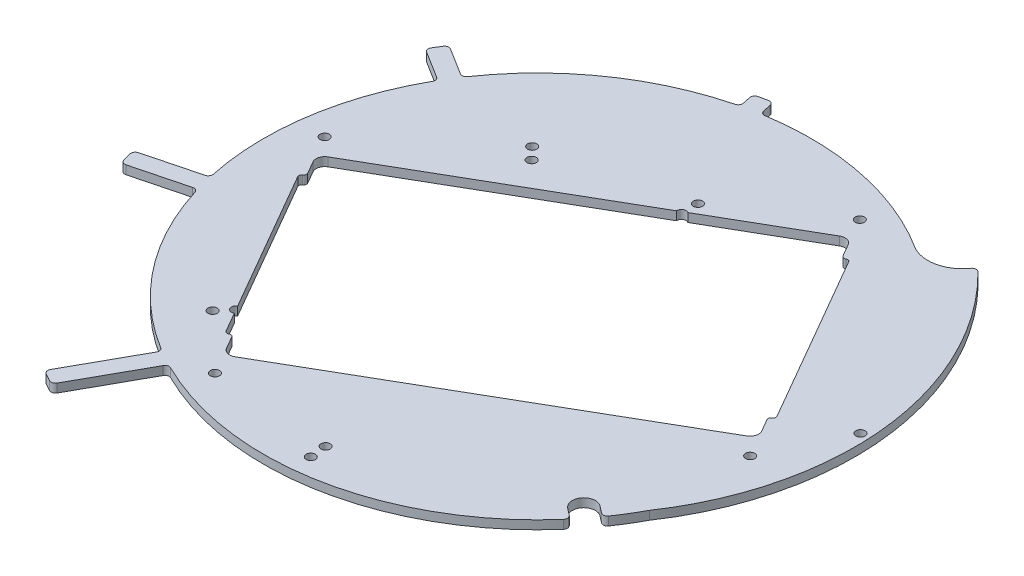
SolidWorks part; units mm, degrees
ref_plane "Ebene vorne" through (0, 0, 0) normal (0, 0, 1) x (1, 0, 0)
ref_plane "Ebene oben" through (0, 0, 0) normal (0, 1, 0) x (1, 0, 0)
ref_plane "Ebene rechts" through (0, 0, 0) normal (1, 0, 0) x (0, 0, -1)
sketch "Skizze1" plane through (0, 0, 0) normal (0, 1, 0) x (1, 0, 0)
  spline S0 degree 4 poles (14.6946, -20.2254) (15.1972, -20.0972) (16.1945, -19.8118) (18.155, -19.1263) (21.9045, -17.3262) (26.5458, -13.9147) (31.2339, -8.2405) (34.3034, -1.3721) (35.6462, 5.1086) (35.8337, 10.8368) (35.3425, 15.6755) (34.2212, 20.452) (32.4895, 25.089) (30.1753, 29.5135) (27.3142, 33.6581) (24.2984, 37.075) (21.3064, 39.8427) (18.4695, 42.0524) (15.8825, 43.7935) (13.1828, 45.3539) (10.3841, 46.7291) (8.0412, 47.6929) (6.2056, 48.3447) (4.9057, 48.759) (4.1664, 48.9823) (3.5009, 49.1701) (2.9324, 49.3228) (2.3788, 49.4662) (1.9696, 49.5678) (1.585, 49.6585) (1.1824, 49.7497) (0.7731, 49.84) (0.2506, 49.9509) (-0.176, 50.0361) (-0.7126, 50.1366) (-1.2516, 50.2331) (-1.7764, 50.322) (-2.3404, 50.4092) (-3.0019, 50.5028) (-3.858, 50.6138) (-4.8637, 50.7239) (-6.0487, 50.8274) (-7.4035, 50.9087) (-8.7603, 50.9537) (-10.1178, 50.9625) (-11.475, 50.9352) (-12.8311, 50.872) (-14.185, 50.7732) (-15.5359, 50.639) (-16.8828, 50.4696) (-18.5604, 50.2144) (-21.309, 49.6989) (-24.3915, 48.921) (-27.7729, 47.8097) (-31.7695, 46.1769) (-34.9991, 44.5869) (-38.1118, 42.7788) (-41.9978, 40.1541) (-45.9692, 37.0083) (-50.3969, 32.7165) (-54.9533, 27.0648) (-58.7999, 20.9088) (-61.8962, 14.3441) (-64.2145, 7.4667) (-65.7383, 0.3714) (-66.4622, -6.8491) (-66.3905, -14.105) (-65.5369, -21.3106) (-63.923, -28.3846) (-61.5784, -35.2506) (-58.5386, -41.8382) (-53.9221, -49.6436) (-47.168, -58.2065) (-37.7396, -66.7961) (-25.2947, -74.3771) (-11.6604, -79.5091) (3.2843, -82.1851) (19.0946, -82.0003) (36.3648, -78.3877) (54.135, -70.3578) (70.574, -57.7146) (84.2397, -40.5569) (93.5043, -20.6856) (97.9802, 0.7684) (97.5541, 22.6716) (92.3547, 43.9462) (80.3282, 68.5258) (58.085, 93.109) (23.6719, 111.5895) (-20.6724, 115.9503) (-63.3844, 103.5087) (-98.6718, 76.5218) (-122.2192, 38.9179) (-131.5042, -4.417) (-125.85, -48.3283) (-106.2669, -87.9909) (-75.1445, -119.3721) (-35.8562, -139.5431) (7.6702, -146.8361) (51.3698, -140.8641) (91.4081, -122.4257) (124.4839, -93.3238) (148.0467, -56.1245) (160.4282, -13.8885) (160.892, 30.1038) (149.6093, 72.6084) (128.6442, 108.7973) (101.0923, 137.2266) (67.9766, 158.7743) (30.8728, 172.5378) (-10.5987, 177.5413) (-54.1378, 171.942) (-105.2309, 151.9976) (-147.9956, 116.5416) (-177.4727, 69.5356) (-193.8883, 5.8675) (-190.4304, -60.5646) (-157.7421, -132.0491) (-89.225, -189.9457) (-2.9015, -213.9008) (85.5525, -200.4114) (161.0378, -152.5558) (211.447, -78.8635) (229.3029, 8.5291) (212.488, 96.0469) (164.0999, 170.796) (91.5801, 222.345) (5.3403, 243.9674) (-82.859, 233.2545) (-161.5374, 192.1036) (-220.9195, 126.1657) (-254.0125, 43.8869) (-257.2482, -44.6901) (-233.9893, -118.6349) (-197.5487, -173.5363) (-158.1112, -211.2478) (-122.0151, -235.7981) (-72.4806, -258.6706) (-18.8569, -270.3704) (36.0125, -270.2335) (89.2898, -258.5247) (129.878, -242.4941) (167.415, -220.2445) (200.9833, -192.3672) (226.1758, -163.6811) (244.3621, -136.5439) (257.0787, -112.5154) (265.7319, -92.562) (274.5884, -66.8593) (282.0045, -35.0464) (285.3007, -2.4946) (284.4351, 30.1581) (280.9666, 57.1207) (276.5638, 78.4183) (270.5627, 99.3216) (263.0017, 119.7125) (253.9277, 139.4764) (243.3959, 158.5035) (231.4693, 176.6887) (218.2181, 193.9324) (203.7194, 210.1412) (188.0566, 225.2279) (171.3189, 239.1124) (153.6007, 251.7215) (137.3261, 261.5812) (122.8899, 269.1582) (110.5687, 274.874) (100.5506, 279.0819) (90.3851, 282.9199) (80.0858, 286.3833) (69.667, 289.4679) (59.1422, 292.1701) (49.8533, 294.1971) (41.8425, 295.6919) (35.1401, 296.7751) (29.7611, 297.5441) (25.0482, 298.1312) (20.9908, 298.5735) (17.6219, 298.9007) (14.927, 299.1378) (12.1541, 299.3528) (9.4847, 299.5398) (6.9207, 299.6987) (4.0187, 299.8442) (1.0689, 299.9667) (-1.1013, 300.0385) (-4.0869, 300.1123) (-7.0224, 300.159) (-9.6213, 300.1693) (-12.3458, 300.1584) (-15.1662, 300.1255) (-17.9045, 300.0646) (-21.3378, 299.9573) (-25.4729, 299.7787) (-30.2807, 299.4963) (-35.7759, 299.0732) (-41.2587, 298.5495) (-46.7331, 297.9257) (-52.1939, 297.2019) (-57.6414, 296.3785) (-63.0725, 295.4558) (-68.4861, 294.4342) (-73.88, 293.314) (-79.2527, 292.0957) (-84.6023, 290.7798) (-89.9271, 289.3667) (-101.848, 285.9698) (-117.516, 280.6722) (-136.6285, 272.7576) (-158.6701, 261.3664) (-177.4812, 249.8542) (-195.4151, 237.0185) (-212.3814, 222.9286) (-228.2949, 207.6598) (-243.0767, 191.293) (-256.654, 173.9142) (-268.9609, 155.6137) (-279.938, 136.4861) (-289.5332, 116.6294) (-297.7017, 96.1445) (-304.4059, 75.1348) (-308.3134, 59.0631) (-310.4129, 48.2443) (-311.3357, 42.8134) knots 0 0 0 0 0 0.000419 0.000839 0.001678 0.003355 0.005034 0.006714 0.007694 0.008675 0.009656 0.010636 0.011652 0.012668 0.013684 0.0147 0.01533 0.01596 0.01659 0.01722 0.01785 0.01848 0.018637 0.018795 0.018952 0.01911 0.019189 0.019268 0.019425 0.019464 0.019504 0.019583 0.01974 0.019877 0.019946 0.020015 0.020152 0.020289 0.020426 0.020563 0.020838 0.021112 0.021387 0.021661 0.021936 0.02221 0.022485 0.022759 0.023034 0.023308 0.023583 0.024131 0.025295 0.025877 0.026458 0.027622 0.028203 0.028785 0.03025 0.031714 0.033178 0.034643 0.036107 0.037571 0.039035 0.0405 0.041964 0.043429 0.044893 0.046357 0.047822 0.049286 0.052215 0.055144 0.058073 0.061002 0.063932 0.067358 0.070784 0.075177 0.07957 0.083963 0.088356 0.09275 0.097143 0.101536 0.10593 0.114717 0.123503 0.13229 0.141076 0.149863 0.15865 0.167436 0.176223 0.18501 0.193797 0.202583 0.21137 0.220157 0.228944 0.23773 0.246517 0.255304 0.264091 0.272877 0.281664 0.288742 0.29582 0.304606 0.313393 0.32218 0.330966 0.348539 0.357326 0.366112 0.383686 0.401259 0.418832 0.436405 0.453979 0.471552 0.489125 0.506698 0.524272 0.541845 0.559418 0.576992 0.594565 0.612138 0.629712 0.647285 0.664859 0.682432 0.691219 0.700005 0.708792 0.717579 0.735152 0.743939 0.752725 0.761512 0.770299 0.779086 0.787872 0.792266 0.796659 0.801052 0.805446 0.814233 0.823019 0.827413 0.831806 0.836199 0.840593 0.844986 0.849379 0.853773 0.858166 0.862559 0.866953 0.871346 0.87574 0.880133 0.884526 0.886723 0.88892 0.891116 0.893313 0.89551 0.897706 0.899903 0.9021 0.903198 0.904297 0.905395 0.906493 0.907042 0.907592 0.908141 0.90869 0.909239 0.909788 0.910337 0.910887 0.911444 0.912001 0.912557 0.913114 0.913671 0.914228 0.914785 0.915342 0.916456 0.91757 0.918684 0.919798 0.920912 0.922026 0.92314 0.924254 0.925368 0.926481 0.927595 0.928709 0.929823 0.930937 0.937621 0.942076 0.946532 0.950988 0.955443 0.959899 0.964355 0.96881 0.973266 0.977722 0.982177 0.986633 0.991089 0.995544 1 1 1 1 1 construction
  spline S1 degree 4 poles (0, 50) (-0.1483, 50.0295) (-0.3717, 50.0727) (-0.7126, 50.1366) (-1.2516, 50.2331) (-1.7764, 50.322) (-2.3404, 50.4092) (-3.0019, 50.5028) (-3.858, 50.6138) (-4.8637, 50.7239) (-6.0487, 50.8274) (-7.4035, 50.9087) (-8.7603, 50.9537) (-10.1178, 50.9625) (-11.475, 50.9352) (-12.8311, 50.872) (-14.185, 50.7732) (-15.5359, 50.639) (-16.8828, 50.4696) (-18.5604, 50.2144) (-21.309, 49.6989) (-24.3915, 48.921) (-27.7729, 47.8097) (-31.7695, 46.1769) (-34.9991, 44.5869) (-38.1118, 42.7788) (-41.9978, 40.1541) (-45.9692, 37.0083) (-50.3969, 32.7165) (-54.9533, 27.0648) (-58.7999, 20.9088) (-61.8962, 14.3441) (-64.2145, 7.4667) (-65.7383, 0.3714) (-66.4622, -6.8491) (-66.3905, -14.105) (-65.5369, -21.3106) (-63.923, -28.3846) (-61.5784, -35.2506) (-58.5386, -41.8382) (-53.9221, -49.6436) (-47.168, -58.2065) (-37.7396, -66.7961) (-25.2947, -74.3771) (-11.6604, -79.5091) (3.2843, -82.1851) (19.0946, -82.0003) (36.3648, -78.3877) (54.135, -70.3578) (70.574, -57.7146) (84.2397, -40.5569) (93.5043, -20.6856) (97.9802, 0.7684) (97.5541, 22.6716) (92.3547, 43.9462) (80.3282, 68.5258) (58.085, 93.109) (23.6719, 111.5895) (-20.6724, 115.9503) (-63.3844, 103.5087) (-98.6718, 76.5218) (-122.2192, 38.9179) (-131.5042, -4.417) (-125.85, -48.3283) (-106.2669, -87.9909) (-75.1445, -119.3721) (-35.8562, -139.5431) (7.6702, -146.8361) (51.3698, -140.8641) (91.4081, -122.4257) (124.4839, -93.3238) (148.0467, -56.1245) (160.4282, -13.8885) (160.892, 30.1038) (149.6093, 72.6084) (128.6442, 108.7973) (101.0923, 137.2266) (67.9766, 158.7743) (30.8728, 172.5378) (-10.5987, 177.5413) (-54.1378, 171.942) (-105.2309, 151.9976) (-147.9956, 116.5416) (-177.4727, 69.5356) (-193.8883, 5.8675) (-190.4304, -60.5646) (-157.7421, -132.0491) (-89.225, -189.9457) (-2.9015, -213.9008) (85.5525, -200.4114) (161.0378, -152.5558) (211.447, -78.8635) (229.3029, 8.5291) (212.488, 96.0469) (164.0999, 170.796) (91.5801, 222.345) (5.3403, 243.9674) (-82.859, 233.2545) (-161.5374, 192.1036) (-220.9195, 126.1657) (-254.0125, 43.8869) (-257.2482, -44.6901) (-233.9893, -118.6349) (-197.5487, -173.5363) (-158.1112, -211.2478) (-122.0151, -235.7981) (-72.4806, -258.6706) (-18.8569, -270.3704) (36.0125, -270.2335) (89.2898, -258.5247) (129.878, -242.4941) (167.415, -220.2445) (200.9833, -192.3672) (226.1758, -163.6811) (244.3621, -136.5439) (257.0787, -112.5154) (265.7319, -92.562) (274.5884, -66.8593) (282.0045, -35.0464) (285.3007, -2.4946) (284.4351, 30.1581) (280.9666, 57.1207) (276.5638, 78.4183) (270.5627, 99.3216) (263.0017, 119.7125) (253.9277, 139.4764) (243.3959, 158.5035) (231.4693, 176.6887) (218.2181, 193.9324) (203.7194, 210.1412) (188.0566, 225.2279) (171.3189, 239.1124) (153.6007, 251.7215) (137.3261, 261.5812) (122.8899, 269.1582) (110.5687, 274.874) (100.5506, 279.0819) (90.3851, 282.9199) (80.0858, 286.3833) (69.667, 289.4679) (59.1422, 292.1701) (49.8533, 294.1971) (41.8425, 295.6919) (35.1401, 296.7751) (29.7611, 297.5441) (25.0482, 298.1312) (20.9908, 298.5735) (17.6219, 298.9007) (14.927, 299.1378) (12.1541, 299.3528) (9.4847, 299.5398) (6.9207, 299.6987) (4.0187, 299.8442) (1.8142, 299.9357) (0.6047, 299.9799) (0, 300) knots 0.01974 0.01974 0.01974 0.01974 0.01974 0.019877 0.019946 0.020015 0.020152 0.020289 0.020426 0.020563 0.020838 0.021112 0.021387 0.021661 0.021936 0.02221 0.022485 0.022759 0.023034 0.023308 0.023583 0.024131 0.025295 0.025877 0.026458 0.027622 0.028203 0.028785 0.03025 0.031714 0.033178 0.034643 0.036107 0.037571 0.039035 0.0405 0.041964 0.043429 0.044893 0.046357 0.047822 0.049286 0.052215 0.055144 0.058073 0.061002 0.063932 0.067358 0.070784 0.075177 0.07957 0.083963 0.088356 0.09275 0.097143 0.101536 0.10593 0.114717 0.123503 0.13229 0.141076 0.149863 0.15865 0.167436 0.176223 0.18501 0.193797 0.202583 0.21137 0.220157 0.228944 0.23773 0.246517 0.255304 0.264091 0.272877 0.281664 0.288742 0.29582 0.304606 0.313393 0.32218 0.330966 0.348539 0.357326 0.366112 0.383686 0.401259 0.418832 0.436405 0.453979 0.471552 0.489125 0.506698 0.524272 0.541845 0.559418 0.576992 0.594565 0.612138 0.629712 0.647285 0.664859 0.682432 0.691219 0.700005 0.708792 0.717579 0.735152 0.743939 0.752725 0.761512 0.770299 0.779086 0.787872 0.792266 0.796659 0.801052 0.805446 0.814233 0.823019 0.827413 0.831806 0.836199 0.840593 0.844986 0.849379 0.853773 0.858166 0.862559 0.866953 0.871346 0.87574 0.880133 0.884526 0.886723 0.88892 0.891116 0.893313 0.89551 0.897706 0.899903 0.9021 0.903198 0.904297 0.905395 0.906493 0.907042 0.907592 0.908141 0.90869 0.909239 0.909788 0.910337 0.910887 0.910887 0.910887 0.910887 0.910887
  point P0 (0, 0)
sketch "Skizze3" plane through (0, 0, 0) normal (0, 1, 0) x (1, 0, 0)
  line L0 (-1.5959, 49.8854) -> (-78.2917, 5.6051)
  line L1 (-22.9202, 96.6291) -> (-22.3443, 93.8164)
  line L2 (-21.7526, 98.3993) -> (-18.813, 99.0034)
  line L3 (-91.5676, 58.8399) -> (-93.1544, 56.294)
  line L4 (-113.5351, -27.851) -> (-112.783, -30.7552)
  line L5 (-61.9583, -108.5299) -> (-59.3353, -109.9859)
  line L6 (-57.2958, -109.4024) -> (-44.1599, -85.7374)
  line L7 (-62.5418, -106.4904) -> (-49.4059, -82.8255)
  line L8 (-110.9549, -31.8312) -> (-92.5649, -27.0691)
  line L9 (-112.459, -26.0228) -> (-94.069, -21.2607)
  line L10 (-92.6749, 54.2276) -> (-83.3928, 48.4422)
  line L11 (-89.5012, 59.3195) -> (-80.2191, 53.5341)
  line L12 (-17.0418, 97.836) -> (-16.4643, 95.0259)
  line L14 (-47.53, -57.6756) -> (-43.6218, -64.4449)
  line L16 (73.8686, -52.127) -> (76.2547, -53.9742)
  line L17 (68.9714, -58.453) -> (71.3575, -60.3002)
  line L27 (-40.8897, -65.1769) -> (-38.3897, -69.507)
  line L41 (-77.6218, -5.5551) -> (-49.13, -54.9044)
  line L42 (-79.3897, 1.507) -> (-76.8897, -2.8231)
  line L43 (79.3897, -1.507) -> (76.8897, 2.8231)
  line L44 (-34.2917, -70.6051) -> (78.2917, -5.6051)
  line L45 (77.6218, 5.5551) -> (43.6218, 64.4449)
  line L46 (40.8897, 65.1769) -> (38.3897, 69.507)
  line L47 (34.2917, 70.6051) -> (0.8972, 51.3248)
  circle A0 centre (-84.8897, 11.0333) radius 1.6
  circle A1 centre (32.8897, 79.0333) radius 1.6
  circle A2 centre (84.8897, -11.0333) radius 1.6
  circle A3 centre (-32.8897, -79.0333) radius 1.6
  arc A4 (-90.7559, -28.0778) -> (-49.929, -80.8214) centre (0, 0) ccw
  arc A5 (-82.8776, 46.436) -> (-92.977, -19.5007) centre (0, 0) ccw
  arc A6 (-42.1823, -85.1214) -> (71.5693, -62.4727) centre (0, 0) ccw
  arc A7 (-44.1599, -85.7374) -> (-42.1823, -85.1214) centre (-42.8484, -86.4654) cw
  arc A8 (-59.3353, -109.9859) -> (-57.2958, -109.4024) centre (-58.6073, -108.6744) ccw
  arc A9 (-61.9583, -108.5299) -> (-62.5418, -106.4904) centre (-61.2303, -107.2184) cw
  arc A10 (-49.4059, -82.8255) -> (-49.929, -80.8214) centre (-50.7174, -82.0975) ccw
  arc A11 (-92.5649, -27.0691) -> (-90.7559, -28.0778) centre (-92.1889, -28.5212) cw
  arc A12 (-112.783, -30.7552) -> (-110.9549, -31.8312) centre (-111.3309, -30.3791) ccw
  arc A13 (-94.069, -21.2607) -> (-92.977, -19.5007) centre (-94.4451, -19.8086) ccw
  arc A14 (-113.5351, -27.851) -> (-112.459, -26.0228) centre (-112.083, -27.4749) cw
  arc A15 (-83.3928, 48.4422) -> (-82.8776, 46.436) centre (-84.1862, 47.1692) cw
  arc A16 (-93.1544, 56.294) -> (-92.6749, 54.2276) centre (-91.8815, 55.5005) ccw
  arc A17 (-91.5676, 58.8399) -> (-89.5012, 59.3195) centre (-90.2946, 58.0465) cw
  arc A18 (-80.2191, 53.5341) -> (-78.1911, 53.9552) centre (-79.4257, 54.8071) ccw
  arc A19 (-18.813, 99.0034) -> (-17.0418, 97.836) centre (-18.5111, 97.5341) cw
  arc A20 (-21.7526, 98.3993) -> (-22.9202, 96.6291) centre (-21.4507, 96.93) ccw
  arc A21 (-22.3443, 93.8164) -> (-23.4436, 92.0619) centre (-23.8138, 93.5155) cw
  arc A22 (-16.4643, 95.0259) -> (-14.762, 93.8461) centre (-14.9951, 95.3278) ccw
  arc A23 (51.1398, 80.0607) -> (-14.762, 93.8461) centre (0, 0) ccw
  arc A24 (-43.6218, -64.4449) -> (-42.2558, -64.8109) centre (-42.7558, -63.9449) ccw
  arc A25 (-42.2558, -64.8109) -> (-40.8897, -65.1769) centre (-41.7558, -65.6769) cw
  arc A26 (-38.3897, -69.507) -> (-34.2917, -70.6051) centre (-35.7917, -68.007) ccw
  arc A27 (-23.4436, 92.0619) -> (-78.1911, 53.9552) centre (0, 0) ccw
  arc A28 (69.0595, 83.8939) -> (66.7734, 83.6844) centre (68.0045, 82.8275) ccw
  arc A29 (66.7734, 83.6844) -> (51.1398, 80.0607) centre (56.9522, 90.52) cw
  circle A30 centre (97.25, 14.9) radius 1.6
  circle A32 centre (8.32, -81.84) radius 1.6
  arc A42 (-77.2558, -4.1891) -> (-77.6218, -5.5551) centre (-76.7558, -5.0551) ccw
  arc A43 (-77.2558, -4.1891) -> (-76.8897, -2.8231) centre (-77.7558, -3.3231) ccw
  arc A44 (-78.2917, 5.6051) -> (-79.3897, 1.507) centre (-76.7917, 3.007) ccw
  arc A45 (77.2558, 4.1891) -> (77.6218, 5.5551) centre (76.7558, 5.0551) ccw
  arc A46 (77.2558, 4.1891) -> (76.8897, 2.8231) centre (77.7558, 3.3231) ccw
  arc A47 (78.2917, -5.6051) -> (79.3897, -1.507) centre (76.7917, -3.007) ccw
  arc A48 (43.6218, 64.4449) -> (42.2558, 64.8109) centre (42.7558, 63.9449) ccw
  arc A49 (40.8897, 65.1769) -> (42.2558, 64.8109) centre (41.7558, 65.6769) ccw
  arc A50 (38.3897, 69.507) -> (34.2917, 70.6051) centre (35.7917, 68.007) ccw
  arc A51 (-49.13, -54.9044) -> (-47.53, -57.6756) centre (-48.33, -56.29) ccw
  circle A52 centre (-42, 40) radius 1.6
  arc A53 (0.8972, 51.3248) -> (-1.5959, 49.8854) centre (0, 50) ccw
  circle A54 centre (0, 55.75) radius 1.6
  circle A55 centre (-45.9655, 44.1638) radius 1.6
  circle A56 centre (-52.0757, -60.6526) radius 1.6
  circle A57 centre (8.9016, -87.5605) radius 1.6
  arc A59 (78.411, -53.635) -> (83.7428, -44.857) centre (0, 0) ccw
  arc A60 (73.8686, -52.127) -> (68.9714, -58.453) centre (71.42, -55.29) ccw
  arc A62 (76.2547, -53.9742) -> (78.411, -53.635) centre (77.1729, -52.7881) ccw
  arc A63 (71.3575, -60.3002) -> (71.5693, -62.4727) centre (70.4393, -61.4863) cw
  spline S0 degree 3 poles (83.7428, -44.857) (85.08, -42.8857) (86.3427, -40.8642) (90.4754, -33.6587) (92.9411, -28.2452) (96.8451, -17.0642) (98.2834, -11.2967) (100.1065, 0.3981) (100.4914, 6.3254) (100.2158, 18.1518) (99.5553, 24.0508) (97.2281, 35.6432) (95.5615, 41.3363) (91.2892, 52.3544) (88.6836, 57.6794) (82.6218, 67.8176) (79.1658, 72.6308) (73.3439, 79.471) (71.2477, 81.7292) (69.0595, 83.8939) knots 0.068743 0.068743 0.068743 0.068743 0.070312 0.070312 0.074219 0.074219 0.078125 0.078125 0.082031 0.082031 0.085937 0.085937 0.089844 0.089844 0.09375 0.09375 0.097656 0.097656 0.099693 0.099693 0.099693 0.099693
  spline S2 degree 3 poles (3903.7256, -759.8806) (-42.2405, 56.3514) (13.4469, 50.5335) (-0.1234, 53.078) (-0.32, 53.114) (-0.7166, 53.1845) (-0.9153, 53.2187) (-1.3018, 53.2828) (-1.49, 53.3127) (-2.0445, 53.3975) (-2.4092, 53.4491) (-3.1633, 53.5489) (-3.5476, 53.5957) (-4.3046, 53.6788) (-4.6812, 53.716) (-5.4375, 53.7827) (-5.8167, 53.8121) (-6.9547, 53.888) (-7.7138, 53.9223) (-11.511, 54.0137) (-14.552, 53.8287) (-20.5572, 52.9655) (-23.5214, 52.2872) (-29.3, 50.4707) (-32.1142, 49.3325) (-37.5292, 46.6377) (-40.13, 45.0812) (-45.0646, 41.5974) (-47.3984, 39.6702) (-51.7555, 35.4974) (-53.7787, 33.2519) (-57.4808, 28.4973) (-59.1597, 25.9883) (-62.1481, 20.7632) (-63.4578, 18.0471) (-65.6918, 12.4643) (-66.6162, 9.5975) (-68.7994, 0.8547) (-69.465, -5.1626) (-69.2373, -17.1545) (-68.3449, -23.1285) (-65.1185, -34.6611) (-62.7853, -40.2193) (-56.8668, -50.6106) (-53.2822, -55.4435) (-45.1003, -64.144) (-40.5036, -68.0116) (-30.5672, -74.6131) (-25.2281, -77.3471) (-14.0895, -81.5827) (-8.2905, -83.0844) (3.487, -84.8214) (9.4653, -85.0569) (21.3343, -84.2856) (27.225, -83.2791) (38.6755, -80.0977) (44.2352, -77.9231) (54.8103, -72.5211) (59.8256, -69.294) (69.1339, -61.9344) (73.4268, -57.8024) (81.1496, -48.8041) (84.5796, -43.9382) (90.4754, -33.6587) (92.9411, -28.2452) (96.8451, -17.0642) (98.2834, -11.2967) (100.1065, 0.3981) (100.4914, 6.3254) (100.2158, 18.1518) (99.5553, 24.0508) (97.2281, 35.6432) (95.5615, 41.3363) (91.2892, 52.3544) (88.6836, 57.6794) (82.6218, 67.8176) (79.1658, 72.6308) (71.5131, 81.622) (67.3166, 85.8) (58.3057, 93.4207) (53.4912, 96.8634) (43.3772, 102.9364) (38.078, 105.5667) (27.1354, 109.9618) (21.492, 111.7266) (10.0022, 114.3604) (4.1559, 115.2293) (-7.5984, 116.0638) (-13.5061, 116.0296) (-25.2464, 115.0712) (-31.0789, 114.1471) (-42.5397, 111.4415) (-48.1678, 109.6602) (-59.0988, 105.291) (-64.4017, 102.7033) (-74.5741, 96.7862) (-79.4435, 93.4568) (-88.6529, 86.1356) (-97.3327, 78.1521) (-104.7905, 69.0219) (-111.5707, 59.4154) (-114.622, 54.3742) (-119.9956, 43.9194) (-122.3181, 38.506) (-126.1983, 27.4132) (-127.7561, 21.734) (-130.0868, 10.2184) (-131.6327, -1.4541) (-131.5981, -13.2248) (-130.7818, -24.9398) (-129.9829, -30.7693) (-127.6259, -42.2709) (-124.5099, -53.6151) (-119.9439, -64.4543) (-114.6988, -74.9526) (-108.7748, -85.1098) (-101.6036, -94.4246) (-93.8725, -103.2472) (-89.727, -107.4124) (-80.9478, -115.1892) (-71.6802, -122.4123) (-61.5887, -128.4262) (-51.1662, -133.795) (-40.4131, -138.5187) (-29.1662, -141.8931) (-17.7572, -144.5737) (-11.9718, -145.5672) (-0.3249, -146.8523) (11.398, -147.4354) (23.1049, -146.6182) (34.7214, -145.1125) (46.2475, -142.9184) (57.4348, -139.3893) (68.3781, -135.2221) (73.7277, -132.8194) (84.1131, -127.4134) (94.1844, -121.4068) (103.5001, -114.2876) (112.3804, -106.6626) (120.8252, -98.5321) (128.2975, -89.5024) (135.2401, -80.0833) (138.4466, -75.1791) (144.2939, -65.0454) (146.9347, -59.816) (153.9663, -43.7395) (157.4625, -32.5037) (161.9389, -9.5462) (162.9194, 2.175) (162.3541, 25.5523) (160.8087, 37.2075) (155.296, 59.9268) (151.3292, 70.99) (141.1807, 92.0449) (134.9995, 102.0361) (120.7171, 120.5309) (112.6161, 129.0342) (94.858, 144.2158) (85.2014, 150.8938) (64.7464, 162.1728) (53.9485, 166.7736) (31.658, 173.7397) (20.1658, 176.1051) (-3.0569, 178.5334) (-14.7866, 178.5964) (-38.0325, 176.4435) (-49.5478, 174.2284) (-71.9354, 167.6295) (-82.8075, 163.2458) (-103.5186, 152.4915) (-113.3574, 146.1211) (-131.6584, 131.6464) (-140.1202, 123.5429) (-155.3849, 105.9036) (-162.1878, 96.368) (-173.9182, 76.2059) (-178.8455, 65.5807) (-186.676, 43.6136) (-189.5792, 32.2718) (-193.2853, 9.2511) (-194.0884, -2.4278) (-193.5897, -25.7377) (-192.2882, -37.368) (-187.6411, -60.2099) (-184.2956, -71.4216) (-175.6836, -93.0808) (-170.4178, -103.5277) (-158.1475, -123.3402) (-151.143, -132.7056) (-135.6204, -150.0833) (-127.1024, -158.0955) (-108.8209, -172.5402) (-99.0582, -178.9724) (-78.5836, -190.0823) (-67.8717, -194.76) (-45.8128, -202.2421) (-34.4665, -205.0465) (-11.4679, -208.7186) (0.1842, -209.5862) (23.4699, -209.3759) (35.1035, -208.2981) (58.033, -204.2429) (69.3283, -201.2659) (91.2789, -193.5079) (101.9342, -188.7269) (122.3286, -177.501) (132.0674, -171.0565) (150.3795, -156.687) (158.9528, -148.7621) (174.7231, -131.6454) (181.92, -122.4537) (194.7655, -103.0469) (200.4137, -92.8324) (210.0315, -71.6438) (214.0011, -60.6697) (220.1762, -38.2362) (222.3818, -26.7772) (224.9884, -3.6581) (225.3894, 8.0017) (224.3894, 31.2429) (222.9885, 42.8243) (218.4309, 65.6353) (215.2745, 76.8643) (207.2919, 98.71) (202.4657, 109.3268) (191.2652, 129.7092) (184.891, 139.4747) (170.7512, 157.9373) (162.9856, 166.6343) (146.2453, 182.7725) (137.2705, 190.2138) (118.3183, 203.6844) (108.3414, 209.7135) (87.6106, 220.2367) (76.8565, 224.7308) (54.807, 232.0971) (43.5116, 234.9692) (20.6252, 239.0408) (9.0344, 240.2402) (-14.1981, 240.951) (-25.8397, 240.4625) (-48.9314, 237.8183) (-60.381, 235.6628) (-82.8534, 229.7394) (-93.8762, 225.9714) (-115.2749, 216.9087) (-125.6506, 211.614) (-145.5496, 199.6142) (-164.5958, 186.2041) (-181.5699, 170.2546) (-197.3476, 153.1991) (-211.9286, 135.0383) (-223.8465, 115.0325) (-234.3266, 94.3002) (-238.8476, 83.5709) (-246.374, 61.5946) (-252.3847, 39.1012) (-255.2677, 15.9995) (-256.5687, -7.1905) (-256.288, -30.4681) (-252.8662, -53.4916) (-247.9129, -76.1804) (-244.6706, -87.3574) (-236.7216, -109.1766) (-227.3085, -130.4607) (-215.1492, -150.3022) (-201.7308, -169.2518) (-194.3922, -178.2803) (-178.5914, -195.2919) (-170.1292, -203.2749) (-152.2321, -218.0631) (-142.7973, -224.8683) (-123.1221, -237.1905) (-112.8819, -242.7073) (-91.7729, -252.3657) (-80.9043, -256.5071) (-58.7236, -263.3521) (-47.4119, -266.0557) (-24.5361, -269.987) (-12.972, -271.2148) (10.2178, -272.1815) (21.8435, -271.9204) (44.9664, -269.9209) (56.4633, -268.1825) (79.1435, -263.2635) (90.3266, -260.0829) (112.2024, -252.3371) (122.8947, -247.772) (143.6211, -237.3361) (153.655, -231.4654) (172.9101, -218.5166) (182.1313, -211.4385) (199.621, -196.1908) (207.8895, -188.0212) (223.3506, -170.7214) (230.5432, -161.5913) (243.7475, -142.5145) (249.7591, -132.5678) (260.5155, -112.0123) (265.2603, -101.4035) (273.4173, -79.6862) (276.8296, -68.5778) (282.2766, -46.0287) (284.3114, -34.5883) (286.9795, -11.5456) (287.6128, 0.0564) (287.4746, 23.2516) (286.7032, 34.8446) (283.7728, 57.8532) (281.6139, 69.2688) (275.9456, 91.7591) (272.4363, 102.8336) (264.1229, 124.485) (259.3189, 135.0617) (248.4897, 155.5697) (242.4646, 165.5008) (229.2828, 184.5808) (222.1263, 193.7295) (206.7862, 211.1203) (198.6026, 219.3623) (181.3259, 234.8293) (172.2327, 242.0543) (153.2652, 255.3923) (143.3908, 261.5053) (122.9984, 272.5406) (112.4804, 277.4628) (90.9453, 286.055) (79.9282, 289.7248) (57.5445, 295.7678) (46.1791, 298.1409) (31.8465, 300.2805) (28.9757, 300.667) (24.6583, 301.1848) (23.2166, 301.3471) (20.3353, 301.6508) (18.8989, 301.7921) (16.7383, 301.9887) (16.0154, 302.0517) (14.5581, 302.173) (13.8237, 302.2311) (12.3664, 302.3418) (11.6447, 302.3943) (10.2247, 302.4934) (9.5276, 302.5399) (8.1258, 302.6281) (7.4157, 302.6699) (5.9374, 302.7502) (5.1695, 302.7887) (3.6253, 302.8607) (2.8503, 302.8941) (1.7667, 302.9379) (1.419, 302.9513) (-23.1164, 303.8599) (13.6034, 299.3669) (-3991.2822, 424.397) knots -0.008741 -0.008741 -0.008741 -0.008741 0.000122 0.000122 0.000244 0.000244 0.000366 0.000366 0.000488 0.000488 0.000732 0.000732 0.000977 0.000977 0.001221 0.001221 0.001465 0.001465 0.001953 0.001953 0.003906 0.003906 0.005859 0.005859 0.007812 0.007812 0.009766 0.009766 0.011719 0.011719 0.013672 0.013672 0.015625 0.015625 0.017578 0.017578 0.019531 0.019531 0.023437 0.023437 0.027344 0.027344 0.03125 0.03125 0.035156 0.035156 0.039062 0.039062 0.042969 0.042969 0.046875 0.046875 0.050781 0.050781 0.054687 0.054687 0.058594 0.058594 0.0625 0.0625 0.066406 0.066406 0.070312 0.070312 0.074219 0.074219 0.078125 0.078125 0.082031 0.082031 0.085937 0.085937 0.089844 0.089844 0.09375 0.09375 0.097656 0.097656 0.101562 0.101562 0.105469 0.105469 0.109375 0.109375 0.113281 0.113281 0.117187 0.117187 0.121094 0.121094 0.125 0.125 0.128906 0.128906 0.132812 0.132812 0.136719 0.136719 0.140625 0.144531 0.144531 0.148437 0.148437 0.152344 0.152344 0.15625 0.15625 0.160156 0.164062 0.164062 0.167969 0.167969 0.171875 0.175781 0.175781 0.179687 0.183594 0.183594 0.1875 0.1875 0.191406 0.195312 0.195312 0.199219 0.203125 0.203125 0.207031 0.207031 0.210937 0.214844 0.214844 0.21875 0.222656 0.222656 0.226562 0.226562 0.230469 0.234375 0.234375 0.238281 0.242187 0.242187 0.246094 0.246094 0.25 0.25 0.257812 0.257812 0.265625 0.265625 0.273437 0.273437 0.28125 0.28125 0.289062 0.289062 0.296875 0.296875 0.304687 0.304687 0.3125 0.3125 0.320312 0.320312 0.328125 0.328125 0.335937 0.335937 0.34375 0.34375 0.351562 0.351562 0.359375 0.359375 0.367187 0.367187 0.375 0.375 0.382812 0.382812 0.390625 0.390625 0.398437 0.398437 0.40625 0.40625 0.414062 0.414062 0.421875 0.421875 0.429687 0.429687 0.4375 0.4375 0.445312 0.445312 0.453125 0.453125 0.460938 0.460938 0.46875 0.46875 0.476563 0.476563 0.484375 0.484375 0.492188 0.492188 0.5 0.5 0.507813 0.507813 0.515625 0.515625 0.523438 0.523438 0.53125 0.53125 0.539063 0.539063 0.546875 0.546875 0.554688 0.554688 0.5625 0.5625 0.570313 0.570313 0.578125 0.578125 0.585938 0.585938 0.59375 0.59375 0.601563 0.601563 0.609375 0.609375 0.617188 0.617188 0.625 0.625 0.632813 0.632813 0.640625 0.640625 0.648438 0.648438 0.65625 0.664063 0.664063 0.671875 0.679688 0.679688 0.6875 0.6875 0.695313 0.703125 0.703125 0.710938 0.71875 0.71875 0.726563 0.726563 0.734375 0.742188 0.742188 0.75 0.75 0.757812 0.757812 0.765625 0.765625 0.773438 0.773438 0.78125 0.78125 0.789062 0.789062 0.796875 0.796875 0.804688 0.804688 0.8125 0.8125 0.820312 0.820312 0.828125 0.828125 0.835938 0.835938 0.84375 0.84375 0.851562 0.851562 0.859375 0.859375 0.867188 0.867188 0.875 0.875 0.882812 0.882812 0.890625 0.890625 0.898438 0.898438 0.90625 0.90625 0.914062 0.914062 0.921875 0.921875 0.929688 0.929688 0.9375 0.9375 0.945312 0.945312 0.953125 0.953125 0.960938 0.960938 0.96875 0.96875 0.976562 0.976562 0.984375 0.984375 0.992188 0.992188 0.994141 0.994141 0.995117 0.995117 0.996094 0.996094 0.996582 0.996582 0.99707 0.99707 0.997559 0.997559 0.998047 0.998047 0.998535 0.998535 0.999023 0.999023 0.999512 0.999512 0.999756 0.999756 1.017341 1.017341 1.017341 1.017341 only from (0.5854, 52.9423) to (0.0994, 302.9984)
  point P10 (-43.4598, -84.4763)
  point P44 (-58.0238, -110.7139)
  point P50 (-63.2698, -107.8019)
  point P56 (-48.7058, -81.5643)
  point P68 (-91.1686, -26.7075)
  point P71 (-112.407, -32.2073)
  point P76 (-113.9111, -26.3989)
  point P81 (-93.9479, 55.021)
  point P84 (-90.7742, 60.1129)
  point P89 (-17.3437, 99.3053)
  point P92 (-23.2209, 98.0976)
  point P95 (-22.0552, 92.4044)
  point P130 (71.42, -55.29)
  point P135 (71.42, -55.29)
  dimension "D4" = 1.5
  dimension "D2" = 1.5
  dimension "D5" = 1.5
  dimension "D1" = 3
extrude "Aufsatz-Linear austragen2" add sketch "Skizze3" along normal blind 3
